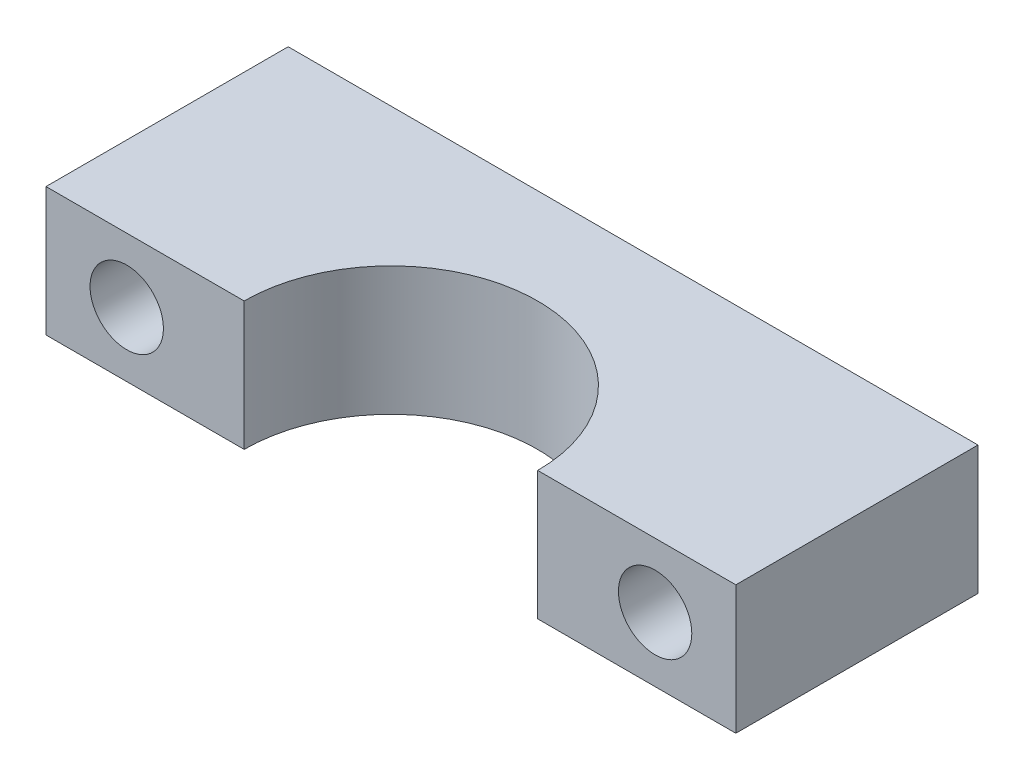
SolidWorks part; units mm, degrees
material "6061-T6 (SS)"
ref_plane "X-Y Datum" through (0, 0, 0) normal (0, 0, 1) x (1, 0, 0)
ref_plane "X-Z Datum" through (0, 0, 0) normal (0, 1, 0) x (1, 0, 0)
ref_plane "Y-Z Datum" through (0, 0, 0) normal (1, 0, 0) x (0, 0, -1)
sketch "Sketch1" plane through (0, 0, 0) normal (0, 1, 0) x (1, 0, 0)
  line L0 (-12.7, 0) -> (-29.845, 0)
  line L1 (-29.845, 0) -> (-29.845, 20.955)
  line L2 (-29.845, 20.955) -> (29.845, 20.955)
  line L3 (29.845, 20.955) -> (29.845, 0)
  line L4 (29.845, 0) -> (12.7, 0)
  line L10 (26.035, 0) -> (26.035, 20.955) construction
  line L11 (19.685, 0) -> (19.685, 20.955) construction
  line L12 (26.035, 10.4775) -> (19.685, 10.4775) construction
  arc A0 (-12.7, 0) -> (12.7, 0) centre (0, 0) cw
  point P16 (0, 0)
  point P17 (-17.7376, 0)
  point P18 (17.7376, 0)
  point P37 (22.86, 10.4775)
  dimension "D1" = 20.955
  dimension "D2" = 12.7
  dimension "D9" = 6.35
  dimension "D3" = 59.69
  dimension "D6" = 22.86
extrude "Boss-Extrude1" add sketch "Sketch1" along normal mid plane 11.1252
sketch "Sketch2" plane through (0, 0, 0) normal (0, 0, 1) x (1, 0, 0)
  line L0 (-22.86, 0) -> (22.86, 0) construction
  circle A0 centre (-22.86, 0) radius 3.175
  circle A1 centre (22.86, 0) radius 3.175
  point P4 (0, 0)
  dimension "D1" = 6.35
  dimension "D2" = 22.86
extrude "Cut-Extrude1" cut sketch "Sketch2" against normal through all
fillet "Fillet1" [suppressed] radius 3.81
fillet "Fillet2" [suppressed] radius 0.254
